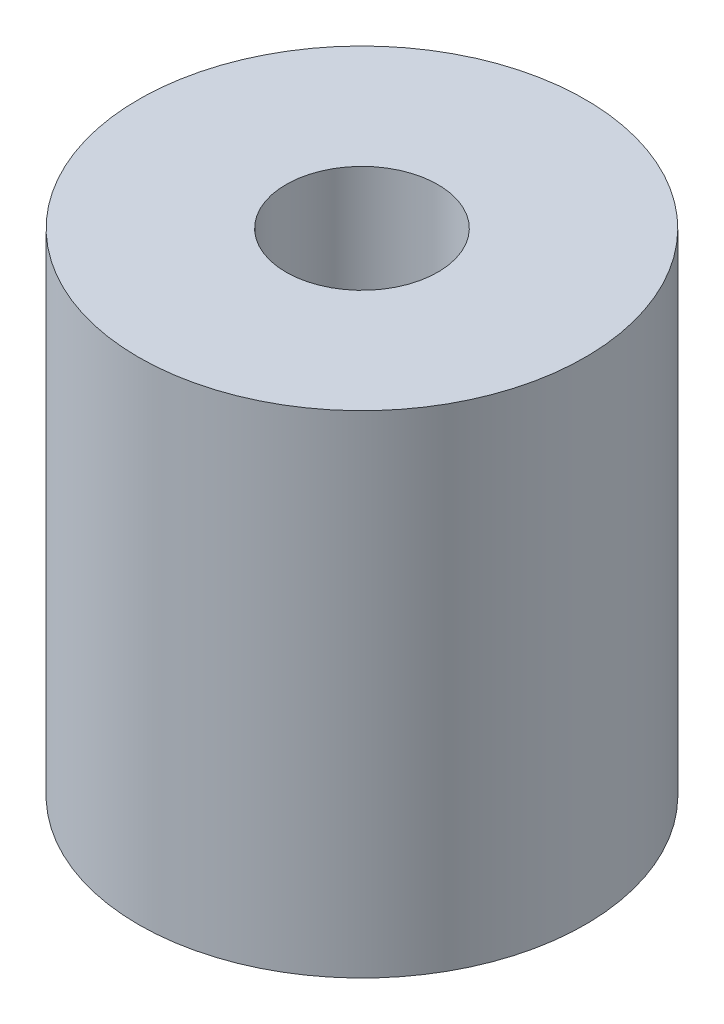
SolidWorks part; units mm, degrees
material "ABS"
ref_plane "Front Plane" through (0, 0, 0) normal (0, 0, 1) x (1, 0, 0)
ref_plane "Top Plane" through (0, 0, 0) normal (0, 1, 0) x (1, 0, 0)
ref_plane "Right Plane" through (0, 0, 0) normal (1, 0, 0) x (0, 0, -1)
other "Configuration Table"
sketch "Sketch1" plane through (0, 0, 0) normal (0, 1, 0) x (1, 0, 0)
  circle A0 centre (0, 0) radius 5
  dimension "D1" = 10
extrude "Boss-Extrude1" add sketch "Sketch1" along normal blind 11
hole_wizard "M3 Clearance Hole1" positions "Sketch2" profile "Sketch3" hole size "M3" standard "ISO" end condition through all
sketch "Sketch2" plane through (0, 11, 0) normal (0, 1, 0) x (1, 0, 0)
  point P0 (0, 0)
sketch "Sketch3" plane through (0, 11, 0) normal (1, 0, 0) x (0, 0, 1)
  line L0 (0, 0) -> (0, 11)
  line L1 (0, 11) -> (1.7, 11)
  line L2 (1.7, 11) -> (1.7, 0)
  line L5 (1.7, 0) -> (0, 0)
  line L11 (0, -6.35) -> (0, 107.95) construction
  dimension "Thru Hole Dia." = 3.4
  dimension "Thru Hole Depth" = 11
